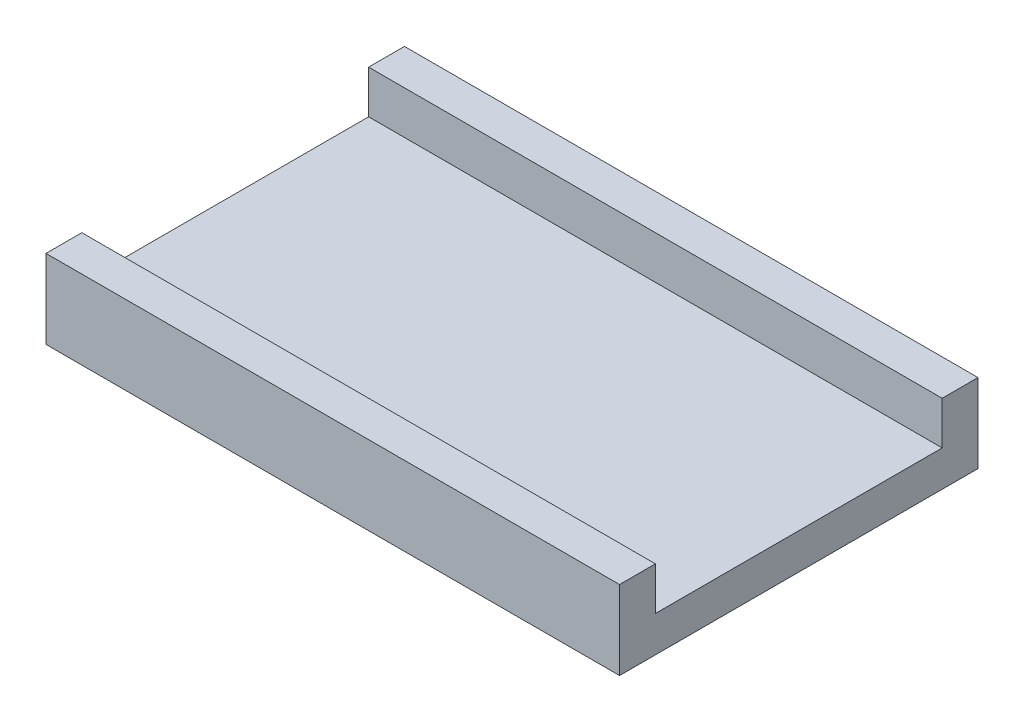
SolidWorks part; units mm, degrees
ref_plane "Front Plane" through (0, 0, 0) normal (0, 0, 1) x (1, 0, 0)
ref_plane "Top Plane" through (0, 0, 0) normal (0, 1, 0) x (1, 0, 0)
ref_plane "Right Plane" through (0, 0, 0) normal (1, 0, 0) x (0, 0, -1)
sketch "Sketch1" plane through (0, 0, 0) normal (0, 1, 0) x (1, 0, 0)
  line L1 (0, 50) -> (80, 50)
  line L2 (0, 50) -> (0, 0)
  line L3 (0, 0) -> (80, 0)
  line L4 (80, 50) -> (80, 0)
  line L5 (0, 50) -> (80, 50)
  line L6 (0, 50) -> (0, 45)
  line L7 (0, 45) -> (80, 45)
  line L8 (80, 50) -> (80, 45)
  line L9 (0, 0) -> (80, 0)
  line L10 (0, 0) -> (0, 5)
  line L11 (0, 5) -> (80, 5)
  line L12 (80, 0) -> (80, 5)
  dimension "D1" = 50
  dimension "D2" = 80
  dimension "D3" = 5
  dimension "D4" = 5
extrude "Boss-Extrude2" add sketch "Sketch1" along normal blind 5 contours L2 L11 L4 L7 | L11 L2 L3 L4 | L2 L7 L4 L1
sketch "Sketch2" plane through (0, 5, 0) normal (0, 1, 0) x (1, 0, 0)
  line L0 (80, 50) -> (80, 0) construction
  line L1 (0, 50) -> (80, 50)
  line L2 (0, 50) -> (0, 45)
  line L3 (0, 45) -> (80, 45)
  line L4 (80, 50) -> (80, 45)
  line L5 (0, 50) -> (0, 0) construction
  line L6 (80, 0) -> (0, 0)
  line L7 (80, 0) -> (80, 5)
  line L8 (80, 5) -> (0, 5)
  line L9 (0, 0) -> (0, 5)
  dimension "D1" = 5
  dimension "D2" = 5
extrude "Boss-Extrude3" add sketch "Sketch2" along normal blind 6
